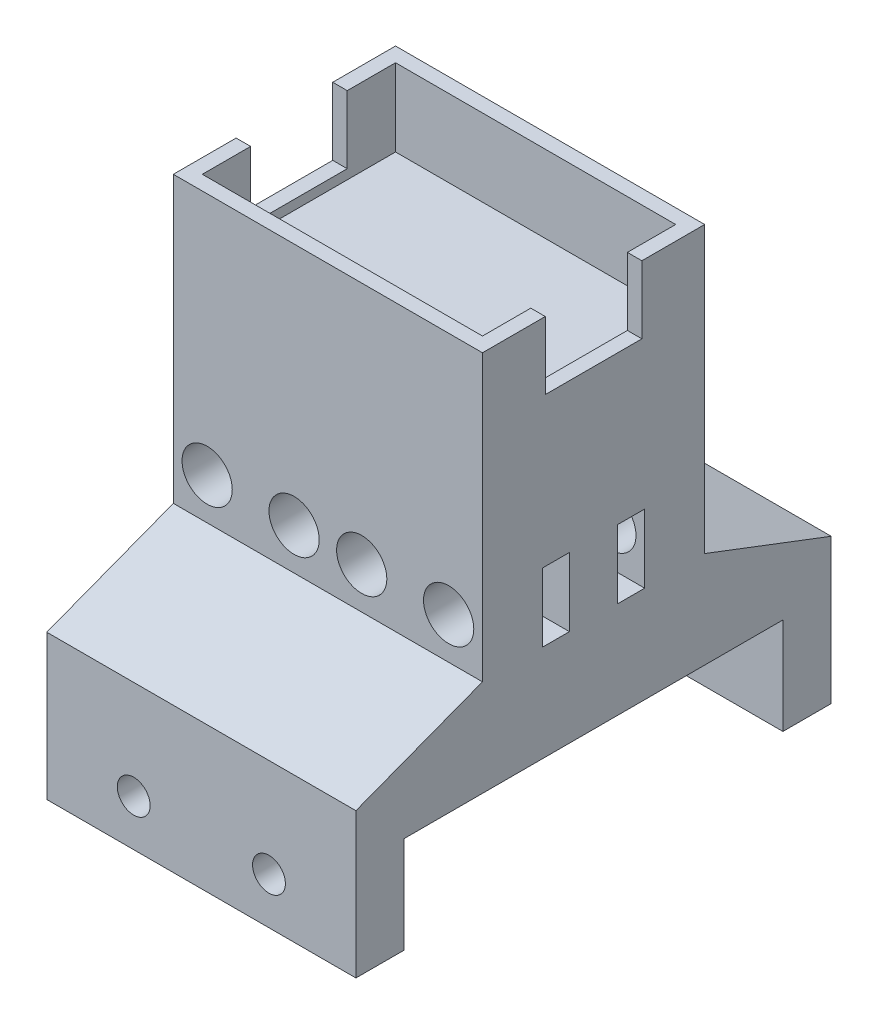
SolidWorks part; units mm, degrees
ref_plane "Front Plane" through (0, 0, 0) normal (0, 0, 1) x (1, 0, 0)
ref_plane "Top Plane" through (0, 0, 0) normal (0, 1, 0) x (1, 0, 0)
ref_plane "Right Plane" through (0, 0, 0) normal (1, 0, 0) x (0, 0, -1)
sketch "Sketch4" plane through (0, 0, 0) normal (0, 1, 0) x (1, 0, 0)
  line L1 (-16, -11.5) -> (16, -11.5)
  line L2 (-16, -11.5) -> (-16, 11.5)
  line L3 (-16, 11.5) -> (16, 11.5)
  line L4 (16, -11.5) -> (16, 11.5)
  line L5 (-16, -11.5) -> (16, 11.5) construction
  line L6 (-16, 11.5) -> (16, -11.5) construction
  point P0 (0, 0)
  dimension "D1" = 32
  dimension "D2" = 23
extrude "Boss-Extrude3" add sketch "Sketch4" along normal blind 19.5
sketch "Sketch5" plane through (0, 19.5, 0) normal (0, 1, 0) x (1, 0, 0)
  line L1 (-14.5, -10) -> (14.5, -10)
  line L2 (-14.5, -10) -> (-14.5, 10)
  line L3 (-14.5, 10) -> (14.5, 10)
  line L4 (14.5, -10) -> (14.5, 10)
  line L5 (-14.5, -10) -> (14.5, 10) construction
  line L6 (-14.5, 10) -> (14.5, -10) construction
  point P0 (0, 0)
  dimension "D1" = 29
  dimension "D2" = 20
extrude "Cut-Extrude2" cut sketch "Sketch5" against normal blind 8
sketch "Sketch7" plane through (16, 0, 0) normal (1, 0, 0) x (0, 0, -1)
  line L1 (-5, 12.5) -> (5, 12.5)
  line L2 (-5, 12.5) -> (-5, 19.5)
  line L3 (-5, 19.5) -> (5, 19.5)
  line L4 (5, 12.5) -> (5, 19.5)
  line L5 (-11.5, 19.5) -> (11.5, 19.5) construction
  point P6 (0, 19.5)
  point P8 (0, 19.5)
  dimension "D1" = 10
  dimension "D2" = 7
extrude "Cut-Extrude4" cut sketch "Sketch7" against normal through all
sketch "Sketch8" plane through (0, 0, 0) normal (0, -1, 0) x (-1, 0, 0)
  line L17 (-16, -11.5) -> (16, -11.5)
  line L18 (-16, -11.5) -> (-16, 11.5)
  line L19 (-16, 11.5) -> (16, 11.5)
  line L20 (16, -11.5) -> (16, 11.5)
  line L21 (-16, -11.5) -> (16, 11.5) construction
  line L22 (-16, 11.5) -> (16, -11.5) construction
  point P4 (0, 0)
extrude "Boss-Extrude4" add sketch "Sketch8" along normal blind 10
ref_plane "Plane1" through (0, 0, 0) normal (0, 0, -1) x (-1, 0, 0)
sketch "Sketch12" plane through (0, 0, -11.5) normal (0, 0, -1) x (-1, 0, 0)
  line L0 (0, 19.5) -> (0, -10) construction
  line L1 (-16, 19.5) -> (16, 19.5) construction
  line L2 (16, -10) -> (-16, -10) construction
  line L3 (-16, 19.5) -> (0, -10) construction
  line L4 (0, 19.5) -> (-16, -10) construction
  line L5 (-8, 4.75) -> (-8, -10) construction
  line L6 (-16, 19.5) -> (-16, -10) construction
  circle A0 centre (-12.5, -5.7269) radius 2.6
  circle A1 centre (-3.5, -5.7269) radius 2.6
  circle A2 centre (3.5, -5.7269) radius 2.6
  circle A3 centre (12.5, -5.7269) radius 2.6
  dimension "D1" = 5.2
  dimension "D3" = 3.5
  dimension "D2" = 4.2731
extrude "Cut-Extrude5" cut sketch "Sketch12" against normal blind 7
pattern_circular "CirPattern1" count 2 over 180 about axis through (0, 11.5, 0) along (0, -1, 0) of "Cut-Extrude5"
sketch "Sketch13" plane through (0, -10, 0) normal (0, -1, 0) x (-1, 0, 0)
  line L0 (16, -11.5) -> (16, 11.5) construction
  line L1 (16, 2.5) -> (1, 2.5)
  line L2 (16, 2.5) -> (16, 5.2916)
  line L3 (16, 5.2916) -> (1, 5.2916)
  line L4 (1, 2.5) -> (1, 5.2916)
  line L5 (16, 2.5) -> (1, 5.2916) construction
  line L6 (16, 5.2916) -> (1, 2.5) construction
  line L7 (13.475, 0) -> (-13.475, 0) construction
  line L8 (0, -11.5) -> (0, 11.5) construction
  line L9 (-16, -11.5) -> (16, -11.5) construction
  line L10 (16, 11.5) -> (-16, 11.5) construction
  line L11 (-16, 5.2916) -> (-1, 5.2916)
  line L12 (-1, 2.5) -> (-1, 5.2916)
  line L13 (-16, 2.5) -> (-1, 2.5)
  line L14 (-16, 2.5) -> (-16, 5.2916)
  line L15 (-16, -2.5) -> (-16, -5.2916)
  line L16 (-16, -2.5) -> (-1, -2.5)
  line L17 (-1, -2.5) -> (-1, -5.2916)
  line L18 (-16, -5.2916) -> (-1, -5.2916)
  line L19 (16, -5.2916) -> (1, -5.2916)
  line L20 (1, -2.5) -> (1, -5.2916)
  line L21 (16, -2.5) -> (1, -2.5)
  line L22 (16, -2.5) -> (16, -5.2916)
  point P4 (8.5, 3.8958)
  dimension "D1" = 15
  dimension "D2" = 2.7916
  dimension "D3" = 2.5
extrude "Cut-Extrude6" cut sketch "Sketch13" against normal blind 7.1
sketch "Sketch14" plane through (0, -10, 0) normal (0, -1, 0) x (-1, 0, 0)
  line L1 (16, 11.5) -> (-16, 11.5)
  line L2 (16, 11.5) -> (16, -11.5)
  line L3 (16, -11.5) -> (-16, -11.5)
  line L4 (-16, 11.5) -> (-16, -11.5)
  line L5 (16, 11.5) -> (-16, -11.5) construction
  line L6 (16, -11.5) -> (-16, 11.5) construction
  point P4 (0, 0)
extrude "Boss-Extrude5" add sketch "Sketch14" along normal blind 5
sketch "Sketch15" plane through (-16, 0, 0) normal (-1, 0, 0) x (0, 0, 1)
  line L1 (-24.6, -15) -> (-24.6, -30)
  line L2 (-24.6, -30) -> (-19.6, -30)
  line L3 (-19.6, -30) -> (-19.6, -20)
  line L4 (-19.6, -20) -> (19.6, -20)
  line L5 (0, -20) -> (0, -15) construction
  line L6 (11.5, -15) -> (-11.5, -15) construction
  line L8 (19.6, -30) -> (19.6, -20)
  line L9 (24.6, -30) -> (19.6, -30)
  line L10 (24.6, -15) -> (24.6, -30)
  line L12 (-24.6, -15) -> (-11.5, -10)
  line L13 (-11.5, 19.5) -> (-11.5, -15) construction
  line L14 (-11.5, -10) -> (-11.5, -15)
  line L15 (-11.5, -15) -> (11.5, -15)
  line L16 (11.5, -10) -> (11.5, -15)
  line L17 (24.6, -15) -> (11.5, -10)
  point P11 (0, 0)
  point P12 (19.6, -20.5409)
  point P22 (-11.5, -10)
  point P23 (0, 0)
  dimension "D1" = 39.2
  dimension "D2" = 10
  dimension "D3" = 5
  dimension "D4" = 5
extrude "Boss-Extrude6" add sketch "Sketch15" against normal up to surface (32 mm away) up to face at (16, -6.45, -3.8958)
sketch "Sketch16" plane through (0, 0, -24.6) normal (0, 0, -1) x (-1, 0, 0)
  line L0 (0, 0) -> (0, 50000) construction
  line L1 (-16, -20) -> (16, -20) construction
  circle A0 centre (7, -25.2) radius 1.7
  circle A1 centre (-7, -25.2) radius 1.7
  dimension "D1" = 3.4
  dimension "D2" = 7
  dimension "D3" = 5.2
extrude "Cut-Extrude7" cut sketch "Sketch16" against normal through all
